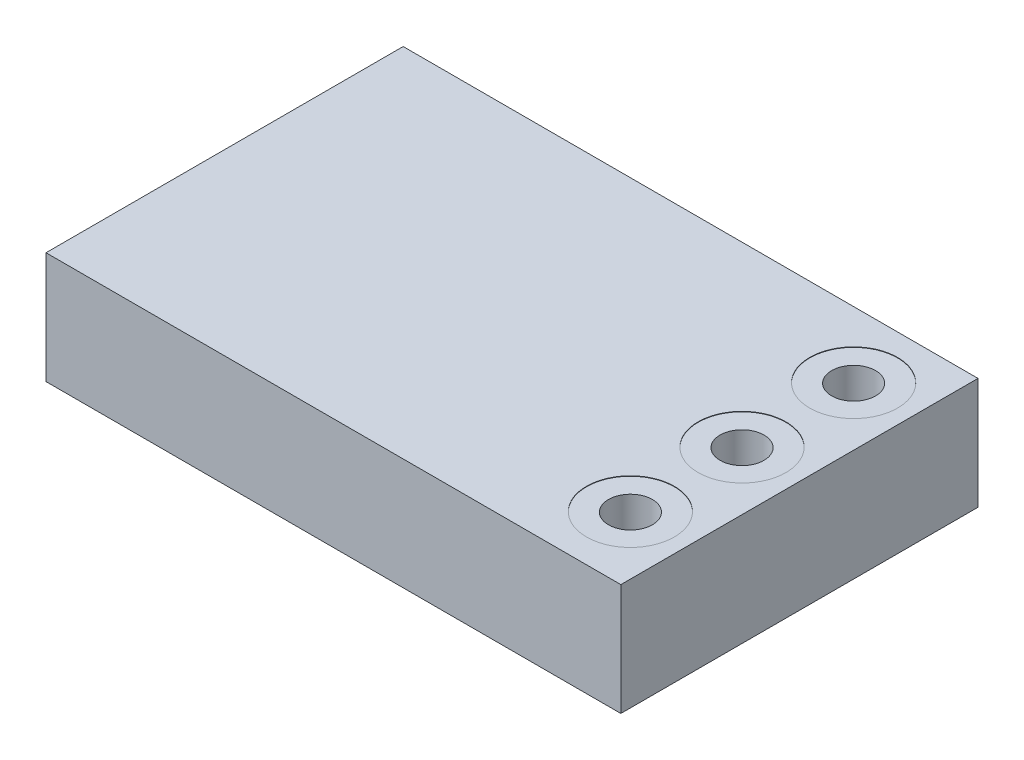
SolidWorks part; units mm, degrees
ref_plane "Front Plane" through (0, 0, 0) normal (0, 0, 1) x (1, 0, 0)
ref_plane "Top Plane" through (0, 0, 0) normal (0, 1, 0) x (1, 0, 0)
ref_plane "Right Plane" through (0, 0, 0) normal (1, 0, 0) x (0, 0, -1)
sketch "Sketch1" plane through (0, 0, 0) normal (0, 1, 0) x (1, 0, 0)
  line L1 (-6.5405, -4.064) -> (6.5405, -4.064)
  line L2 (-6.5405, -4.064) -> (-6.5405, 4.064)
  line L3 (-6.5405, 4.064) -> (6.5405, 4.064)
  line L4 (6.5405, -4.064) -> (6.5405, 4.064)
  line L5 (-6.5405, -4.064) -> (6.5405, 4.064) construction
  line L6 (-6.5405, 4.064) -> (6.5405, -4.064) construction
  point P0 (0, 0)
  dimension "D1" = 8.128
  dimension "D2" = 13.081
extrude "Boss-Extrude1" add sketch "Sketch1" along normal blind 2.54
sketch "Sketch2" plane through (0, 2.54, 0) normal (0, 1, 0) x (1, 0, 0)
  circle A0 centre (5.2113, 2.5633) radius 0.5
  circle A1 centre (5.2113, 0.0233) radius 0.5
  circle A2 centre (5.2113, -2.5167) radius 0.5
  dimension "D1" = 1
  dimension "D3" = 2.54
  dimension "D2" = 3
extrude "Cut-Extrude1" cut sketch "Sketch2" against normal through all
sketch "Sketch3" plane through (0, 2.54, 0) normal (0, 1, 0) x (1, 0, 0)
  circle A0 centre (5.2113, 2.5633) radius 1
  circle A1 centre (5.2113, 0.0233) radius 1
  circle A2 centre (5.2113, -2.5167) radius 1
  dimension "D1" = 2
extrude "Cut-Extrude2" cut sketch "Sketch3" against normal blind 0.01
